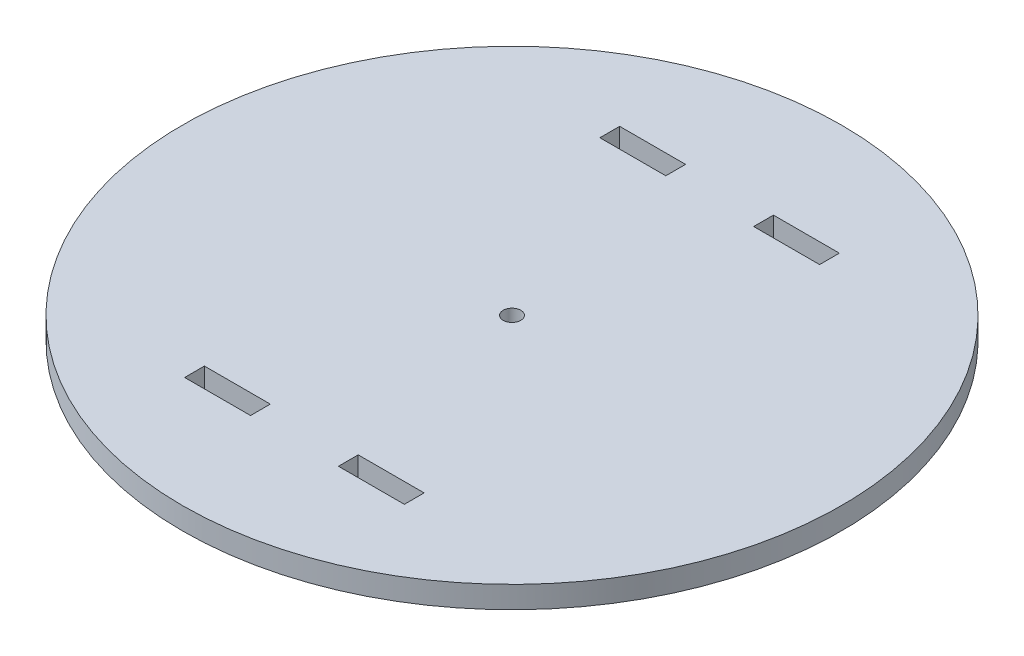
SolidWorks part; units mm, degrees
material "Balsa"
ref_plane "Front Plane" through (0, 0, 0) normal (0, 0, 1) x (1, 0, 0)
ref_plane "Top Plane" through (0, 0, 0) normal (0, 1, 0) x (1, 0, 0)
ref_plane "Right Plane" through (0, 0, 0) normal (1, 0, 0) x (0, 0, -1)
sketch "Sketch1" plane through (0, 0, 0) normal (0, 1, 0) x (1, 0, 0)
  circle A0 centre (0, 0) radius 75
  dimension "D1" = 150
extrude "Boss-Extrude1" add sketch "Sketch1" along normal blind 5
sketch "Sketch2" plane through (0, 5, 0) normal (0, 1, 0) x (1, 0, 0)
  line L0 (-10, 49.5) -> (-10, 45)
  line L1 (-25, 49.5) -> (25, 49.5)
  line L2 (-25, 49.5) -> (-25, 45)
  line L3 (-25, 45) -> (25, 45)
  line L4 (25, 49.5) -> (25, 45)
  line L5 (10, 49.5) -> (10, 45)
  point P8 (0, 45)
  dimension "D1" = 15
  dimension "D2" = 15
  dimension "D3" = 20
  dimension "D4" = 4.5
  dimension "D5" = 45
extrude "Cut-Extrude1" cut sketch "Sketch2" against normal blind 10 contours L2 L3 L0 L1 | L1 L5 L3 L4
mirror "Mirror1" about plane through (0, 0, 0) normal (0, 0, 1) of "Cut-Extrude1"
sketch "Sketch3" plane through (0, 5, 0) normal (0, 1, 0) x (1, 0, 0)
  circle A0 centre (0, 0) radius 2
  dimension "D1" = 4
extrude "Cut-Extrude2" cut sketch "Sketch3" against normal blind 10
